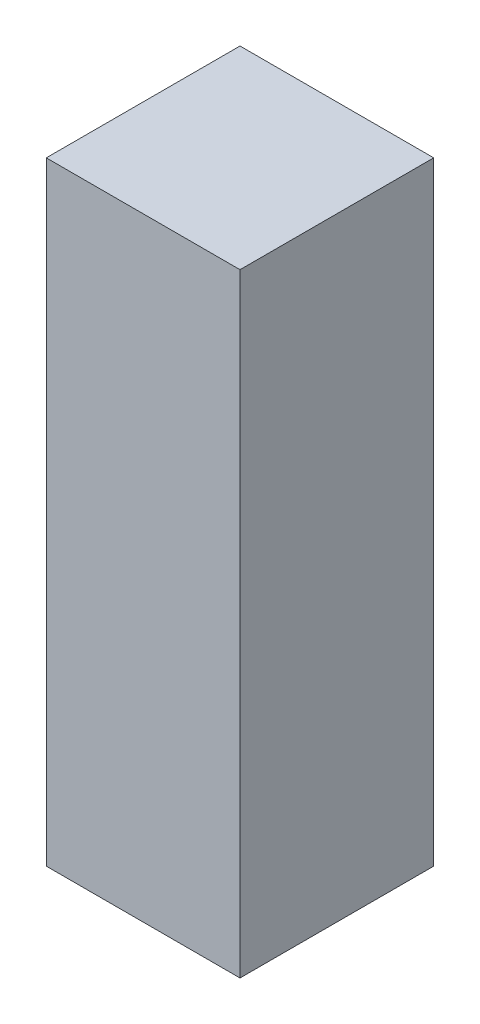
SolidWorks part; units mm, degrees
ref_plane "Alzado" through (0, 0, 0) normal (0, 0, 1) x (1, 0, 0)
ref_plane "Planta" through (0, 0, 0) normal (0, 1, 0) x (1, 0, 0)
ref_plane "Vista lateral" through (0, 0, 0) normal (1, 0, 0) x (0, 0, -1)
sketch "Croquis1" plane through (0, 0, 0) normal (0, 0, 1) x (1, 0, 0)
  line L1 (0, 0) -> (48, 0)
  line L2 (0, 0) -> (0, 152)
  line L3 (0, 152) -> (48, 152)
  line L4 (48, 0) -> (48, 152)
  dimension "D1" = 152
  dimension "D2" = 48
extrude "Saliente-Extruir1" add sketch "Croquis1" along normal blind 48
